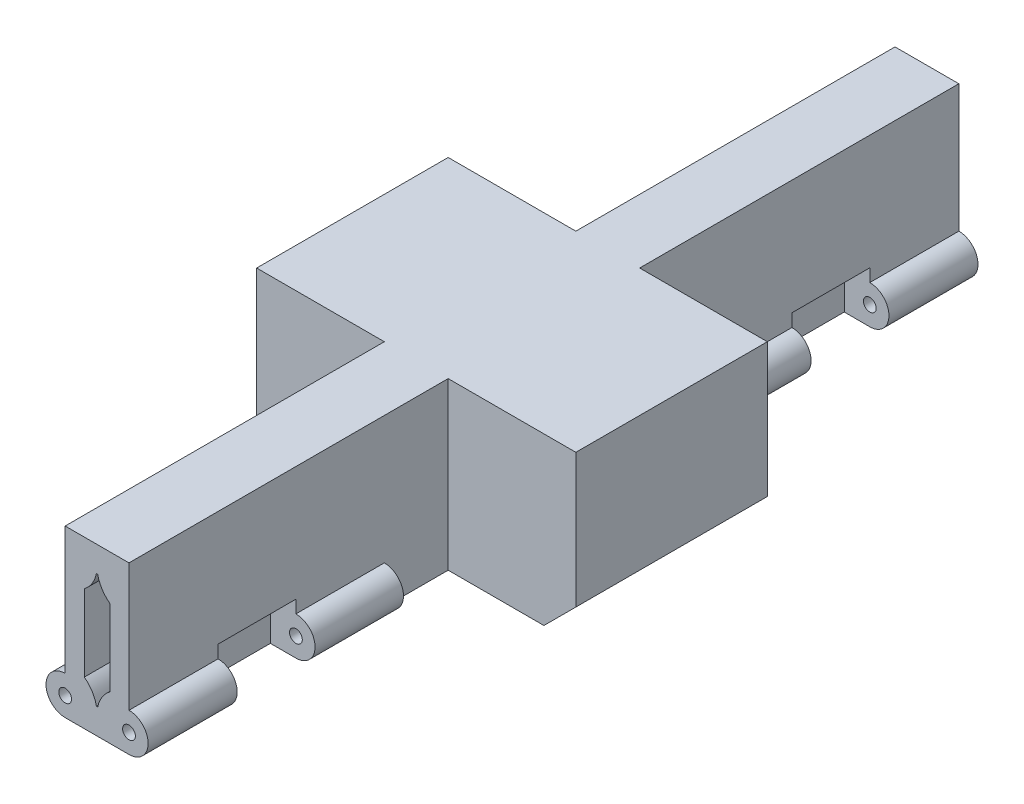
SolidWorks part; units mm, degrees
material "ABS"
ref_plane "Спереди" through (0, 0, 0) normal (0, 0, 1) x (1, 0, 0)
ref_plane "Сверху" through (0, 0, 0) normal (0, 1, 0) x (1, 0, 0)
ref_plane "Справа" through (0, 0, 0) normal (1, 0, 0) x (0, 0, -1)
sketch "Эскиз1" plane through (0, 0, 0) normal (0, 0, 1) x (1, 0, 0)
  line L0 (0, 30.7154) -> (0, -31.2898) construction
  line L2 (25, -13.2872) -> (-25, -13.2872)
  line L3 (25, -13.2872) -> (25, 12.7128)
  line L4 (25, 12.7128) -> (-25, 12.7128)
  line L5 (-25, -13.2872) -> (-25, 12.7128)
  line L6 (25, -13.2872) -> (-25, 12.7128) construction
  line L7 (25, 12.7128) -> (-25, -13.2872) construction
  point P3 (0, -0.2872)
  dimension "D1" = 50
  dimension "D2" = 26
extrude "Бобышка-Вытянуть1" add sketch "Эскиз1" along normal mid plane 130
sketch "Эскиз7" plane through (0, 0, 65) normal (0, 0, 1) x (1, 0, 0)
  line L0 (0, 12.7128) -> (0, -13.2872) construction
  line L1 (-25, -13.2872) -> (-5, -13.2872)
  line L2 (-25, -13.2872) -> (-25, 12.7128)
  line L3 (-25, 12.7128) -> (-5, 12.7128)
  line L4 (-5, -13.2872) -> (-5, 12.7128)
  line L5 (25, 12.7128) -> (-25, 12.7128) construction
  line L6 (-25, -13.2872) -> (25, -13.2872) construction
  dimension "D1" = 26
  dimension "D2" = 5
extrude "Вырез-Вытянуть5" cut sketch "Эскиз7" against normal blind 50
sketch "Эскиз4" plane through (0, 0, 65) normal (0, 0, 1) x (1, 0, 0)
  line L0 (-27.9128, 0) -> (25.9263, 0) construction
  line L1 (-5, -13.2872) -> (-5, 12.7128) construction
  line L2 (-25, -13.2872) -> (-5, -13.2872) construction
  circle A1 centre (-5, -10.2872) radius 3
  dimension "D1" = 6
  dimension "D3" = 3
extrude "Бобышка-Вытянуть3" add sketch "Эскиз4" against normal blind 40
sketch "Эскиз5" plane through (-5, 0, 0) normal (-1, 0, 0) x (0, 0, 1)
  line L0 (65, -7.2872) -> (65, 12.7128) construction
  line L5 (25, -13.2872) -> (65, -13.2872) construction
  line L6 (38.85, -13.2872) -> (51.05, -13.2872)
  line L11 (38.85, -13.2872) -> (38.85, -5.2872)
  line L12 (38.85, -5.2872) -> (51.05, -5.2872)
  line L13 (51.05, -13.2872) -> (51.05, -5.2872)
  dimension "D4" = 8
  dimension "D1" = 13.95
  dimension "D2" = 12.2
extrude "Вырез-Вытянуть3" cut sketch "Эскиз5" against normal mid plane 8
sketch "Эскиз6" plane through (0, 0, 65) normal (0, 0, 1) x (1, 0, 0)
  circle A1 centre (-5, -10.2872) radius 1
  arc A2 (-5, -7.2872) -> (-5, -13.2872) centre (-5, -10.2872) ccw construction
  point P0 (-5, -10.2872)
  dimension "D1" = 2
extrude "Вырез-Вытянуть4" cut sketch "Эскиз6" against normal blind 40
mirror "Зеркальное отражение1" about plane through (0, 0, 0) normal (0, 0, 1) of "Вырез-Вытянуть5", "Вырез-Вытянуть4", "Вырез-Вытянуть3", "Бобышка-Вытянуть3"
mirror "Зеркальное отражение2" about plane through (0, 0, 0) normal (1, 0, 0) of "Зеркальное отражение1", "Вырез-Вытянуть5", "Бобышка-Вытянуть3", "Вырез-Вытянуть3", "Вырез-Вытянуть4"
sketch "Эскиз9" plane through (0, 0, 0) normal (0, 0, 1) x (1, 0, 0)
  line L0 (0, 12.7128) -> (0, -13.2872) construction
  line L3 (-5, -9.2872) -> (-5, -11.2872) construction
  line L4 (5, -9.2872) -> (5, -11.2872) construction
  line L5 (-2, 13.7128) -> (-2, -6.2872)
  line L6 (-0.101, -9.2872) -> (0.101, -9.2872)
  line L7 (2, -6.2872) -> (2, 13.7128)
  line L8 (-0.101, 8.7128) -> (0.101, 8.7128)
  line L9 (5, 12.7128) -> (-5, 12.7128) construction
  line L10 (-5, -7.2872) -> (-5, 12.7128) construction
  line L11 (-5, -13.2872) -> (5, -13.2872) construction
  line L13 (-5, 12.7128) -> (-25, 12.7128) construction
  line L14 (-5, -13.2872) -> (-5, 12.7128) construction
  line L15 (5, 12.7128) -> (-5, 12.7128) construction
  circle A0 centre (-5, 9.7128) radius 5
  circle A1 centre (5, 9.7128) radius 5
  circle A2 centre (-5, -10.2872) radius 5
  circle A3 centre (5, -10.2872) radius 5
  point P5 (0, 0)
  point P6 (0, 0)
  point P33 (0, 0)
  point P34 (0, 0)
  point P35 (-7, 9.7128)
  point P38 (0, 12.7128)
  point P41 (0, -13.2872)
  dimension "D1" = 10
  dimension "D2" = 4
  dimension "D3" = 3
  dimension "D4" = 4
  dimension "D5" = 3
extrude "Вырез-Вытянуть7" cut sketch "Эскиз9" against normal through all both and the other way through all contours L0 L8 A0 L5 A2 L6 | L8 L0 L6 A3 L7 A1
sketch "Эскиз10" plane through (0, 0, 15) normal (0, 0, 1) x (1, 0, 0)
  line L0 (25, 12.7128) -> (25, -13.2872) construction
  line L2 (-5, -13.2872) -> (5, -13.2872) construction
  line L4 (-25, 12.7128) -> (-25, -13.2872) construction
  line L5 (25, 12.7128) -> (25, -8.2872)
  line L6 (-25, -8.2872) -> (-20, -13.2872)
  line L7 (-20, -13.2872) -> (20, -13.2872)
  line L8 (25, -8.2872) -> (20, -13.2872)
  line L9 (-25, 12.7128) -> (-25, -8.2872)
  line L10 (-25, -8.2872) -> (-25, -13.2872)
  line L11 (-25, -13.2872) -> (-20, -13.2872)
  line L12 (20, -13.2872) -> (25, -13.2872)
  line L13 (25, -13.2872) -> (25, -8.2872)
  line M4 (-25, 12.7128) -> (-25, -13.2872)
  line M5 (-25, -13.2872) -> (-5, -13.2872)
extrude "Вырез-Вытянуть8" cut sketch "Эскиз10" against normal up to next contours L6 M4 M5 | L12 L13 L8
equation "\"D4@Эскиз5\"=\"D2@Эскиз5\""
equation "\"D4@Эскиз9\"=\"D2@Эскиз9\""
